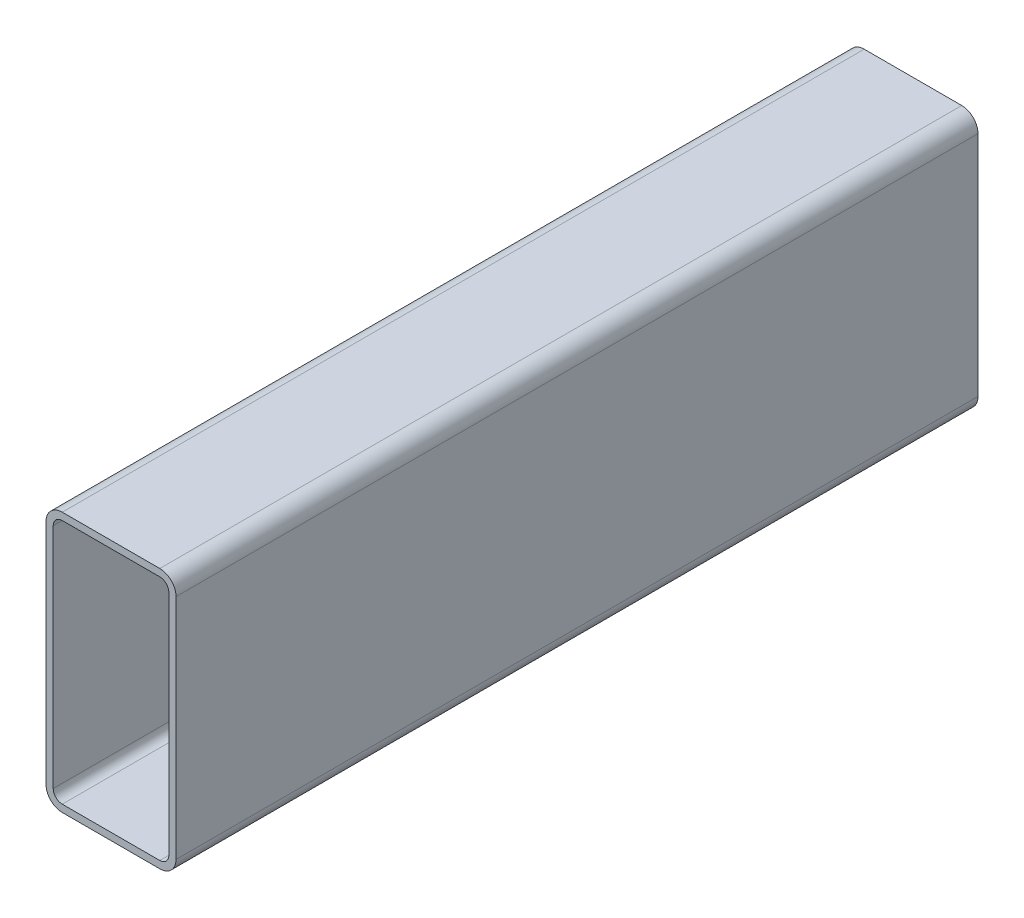
SolidWorks part; units mm, degrees
material "Plain Carbon Steel"
ref_plane "Front Plane" through (0, 0, 0) normal (0, 0, 1) x (1, 0, 0)
ref_plane "Top Plane" through (0, 0, 0) normal (0, 1, 0) x (1, 0, 0)
ref_plane "Right Plane" through (0, 0, 0) normal (1, 0, 0) x (0, 0, -1)
sketch "Sketch1" plane through (0, 0, 0) normal (1, 0, 0) x (0, 0, -1)
  line L0 (0, 0) -> (-234.95, 0)
  dimension "D1" = 234.95
other "Structural Member1"
ref_plane "Plane1" through (0, 0, 0) normal (0, 0, 1) x (1, 0, 0)
sketch "Sketch13" plane through (0, 0, 0) normal (0, 0, 1) x (1, 0, 0)
  line L0 (-14.2875, -35.9842) -> (14.2875, -35.9842)
  line L1 (-16.9342, -33.3375) -> (-16.9342, 33.3375)
  line L2 (14.2875, 35.9842) -> (-14.2875, 35.9842)
  line L3 (16.9342, 33.3375) -> (16.9342, -33.3375)
  line L4 (-14.2875, -38.1) -> (14.2875, -38.1)
  line L5 (-19.05, -33.3375) -> (-19.05, 33.3375)
  line L6 (14.2875, 38.1) -> (-14.2875, 38.1)
  line L7 (19.05, 33.3375) -> (19.05, -33.3375)
  line L8 (0, 0) -> (19.05, 0) construction
  line L9 (0, 0) -> (0, 38.1) construction
  arc A0 (19.05, 33.3375) -> (14.2875, 38.1) centre (14.2875, 33.3375) ccw
  arc A1 (14.2875, -38.1) -> (19.05, -33.3375) centre (14.2875, -33.3375) ccw
  arc A2 (-19.05, -33.3375) -> (-14.2875, -38.1) centre (-14.2875, -33.3375) ccw
  arc A3 (-14.2875, 38.1) -> (-19.05, 33.3375) centre (-14.2875, 33.3375) ccw
  arc A4 (-14.2875, 35.9842) -> (-16.9342, 33.3375) centre (-14.2875, 33.3375) ccw
  arc A5 (16.9342, 33.3375) -> (14.2875, 35.9842) centre (14.2875, 33.3375) ccw
  arc A6 (14.2875, -35.9842) -> (16.9342, -33.3375) centre (14.2875, -33.3375) ccw
  arc A7 (-16.9342, -33.3375) -> (-14.2875, -35.9842) centre (-14.2875, -33.3375) ccw
  point P3 (0, -38.1)
  point P4 (-19.05, 0)
  point P5 (0, 0)
  point P6 (19.05, -38.1)
  point P7 (-19.05, -38.1)
  point P8 (-19.05, 38.1)
  point P33 (0, 0)
  point P35 (19.05, 38.1)
  point P36 (19.05, 0)
  point P37 (0, 38.1)
  dimension "D1" = 4.7625
  dimension "Thickness" = 2.1158
  dimension "V_leg" = 76.2
  dimension "H_leg" = 38.1
sketch "Sketch14" plane through (19.05, 0, 0) normal (1, 0, 0) x (0, 0, -1)
  line L0 (-234.95, 0) -> (0, 0) construction
  line L1 (0, -33.3375) -> (0, 33.3375) construction
  line L2 (-203.9026, -19.7526) -> (-164.3974, 19.7526) construction
  line L3 (-200.025, 15.875) -> (-200.025, 0) construction
  line L4 (-168.275, -15.875) -> (-168.275, 0) construction
  circle A0 centre (-200.025, 15.875) radius 12.7
  circle A1 centre (-168.275, -15.875) radius 12.7
  point P11 (-184.15, 0)
  dimension "D4" = 25.4
  dimension "D1" = 45
  dimension "D2" = 31.75
  dimension "D3" = 50.8
